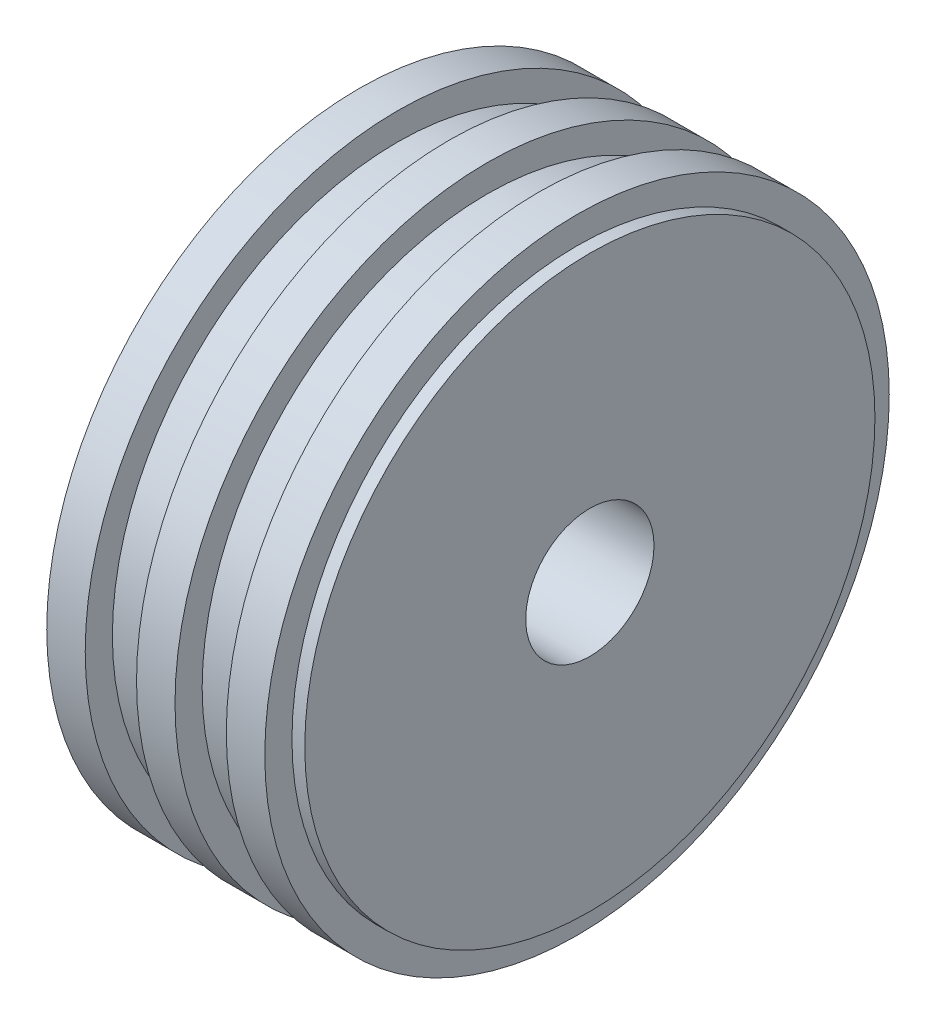
SolidWorks part; units mm, degrees
ref_plane "Front Plane" through (0, 0, 0) normal (0, 0, 1) x (1, 0, 0)
ref_plane "Top Plane" through (0, 0, 0) normal (0, 1, 0) x (1, 0, 0)
ref_plane "Right Plane" through (0, 0, 0) normal (1, 0, 0) x (0, 0, -1)
sketch "Sketch1" plane through (0, 0, 0) normal (0, 1, 0) x (1, 0, 0)
  line L0 (0, 0) -> (-57, 0) construction
  line L1 (-57, 15) -> (-57, 66.675)
  line L2 (-57, 66.675) -> (-54, 66.675)
  line L3 (-54, 66.675) -> (-54, 73.025)
  line L4 (-54, 73.025) -> (-45, 73.025)
  line L5 (-45, 73.025) -> (-45, 66.675)
  line L6 (-45, 66.675) -> (-33, 66.675)
  line L7 (-33, 66.675) -> (-33, 73.025)
  line L8 (-33, 73.025) -> (-24, 73.025)
  line L9 (-24, 73.025) -> (-24, 66.675)
  line L10 (-24, 66.675) -> (-12, 66.675)
  line L11 (-12, 66.675) -> (-12, 73.025)
  line L12 (-12, 73.025) -> (-3, 73.025)
  line L13 (-3, 73.025) -> (-3, 66.675)
  line L14 (-3, 66.675) -> (0, 66.675)
  line L15 (0, 66.675) -> (0, 15)
  line L17 (-57, 15) -> (0, 15)
  point P6 (0, 0)
  dimension "D1" = 57
  dimension "D2" = 6.35
  dimension "D3" = 12
  dimension "D4" = 12
  dimension "D5" = 3
  dimension "D6" = 3
  dimension "D7" = 9
  dimension "D8" = 9
  dimension "D9" = 9
  dimension "D10" = 66.675
  dimension "D11" = 66.675
  dimension "D12" = 73.025
revolve "Revolve1" add sketch "Sketch1" angle 360 about L0
